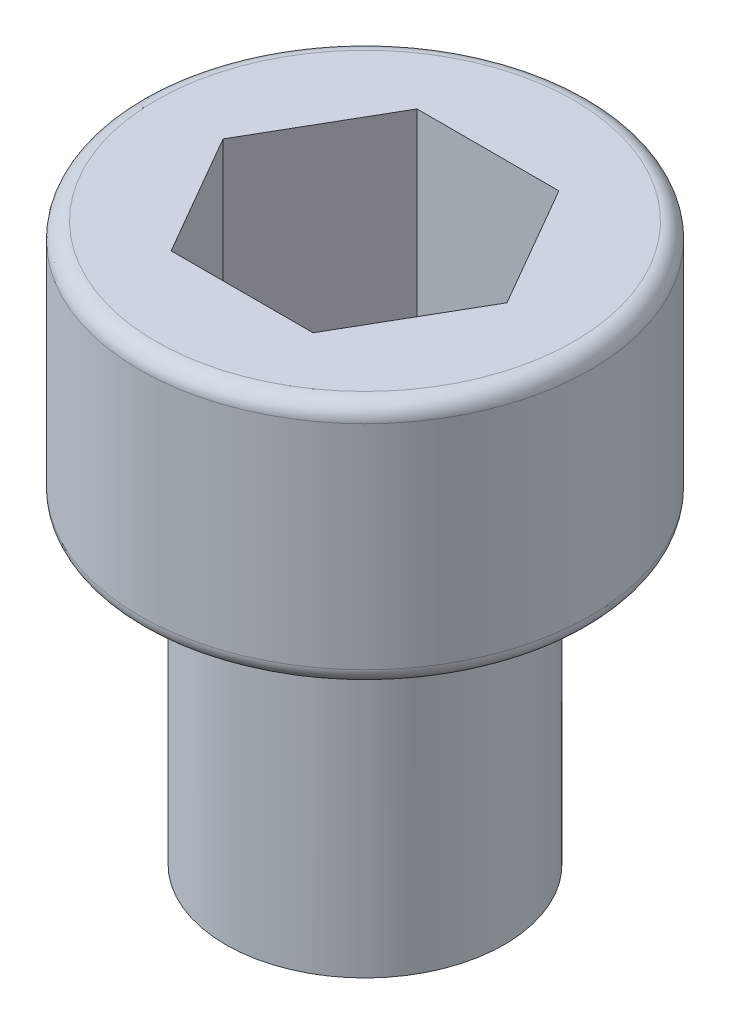
SolidWorks part; units mm, degrees
ref_plane "Front Plane" through (0, 0, 0) normal (0, 0, 1) x (1, 0, 0)
ref_plane "Top Plane" through (0, 0, 0) normal (0, 1, 0) x (1, 0, 0)
ref_plane "Right Plane" through (0, 0, 0) normal (1, 0, 0) x (0, 0, -1)
sketch "Sketch1" plane through (0, 0, 0) normal (0, 0, 1) x (1, 0, 0)
  line L0 (2.159, 0) -> (2.159, 4.826)
  line L1 (2.159, 4.826) -> (3.4925, 4.826)
  line L2 (3.4925, 4.826) -> (3.4925, 8.636)
  line L3 (3.4925, 8.636) -> (0, 8.636)
  line L4 (0, 8.636) -> (0, 0)
  line L5 (0, 0) -> (2.159, 0)
  line L6 (0, 0) -> (0, -24.0158) construction
  dimension "D1" = 4.318
  dimension "D2" = 4.826
  dimension "D3" = 3.81
  dimension "D4" = 6.985
revolve "Revolve1" add sketch "Sketch1" angle 360 about L6
fillet "Fillet1" radius 0.254 2 edges at (0, 8.636, 3.4925) (0, 4.826, 3.4925)
sketch "Sketch2" plane through (0, 8.636, 0) normal (0, 1, 0) x (1, 0, 0)
  line L1 (1.0999, 1.905) -> (-1.0999, 1.905)
  line L2 (-1.0999, 1.905) -> (-2.1997, 0)
  line L3 (-2.1997, 0) -> (-1.0999, -1.905)
  line L4 (-1.0999, -1.905) -> (1.0999, -1.905)
  line L5 (1.0999, -1.905) -> (2.1997, 0)
  line L6 (2.1997, 0) -> (1.0999, 1.905)
  circle A0 centre (0, 0) radius 1.905 construction
  dimension "D1" = 3.81
extrude "Cut-Extrude1" cut sketch "Sketch2" against normal blind 3.81
